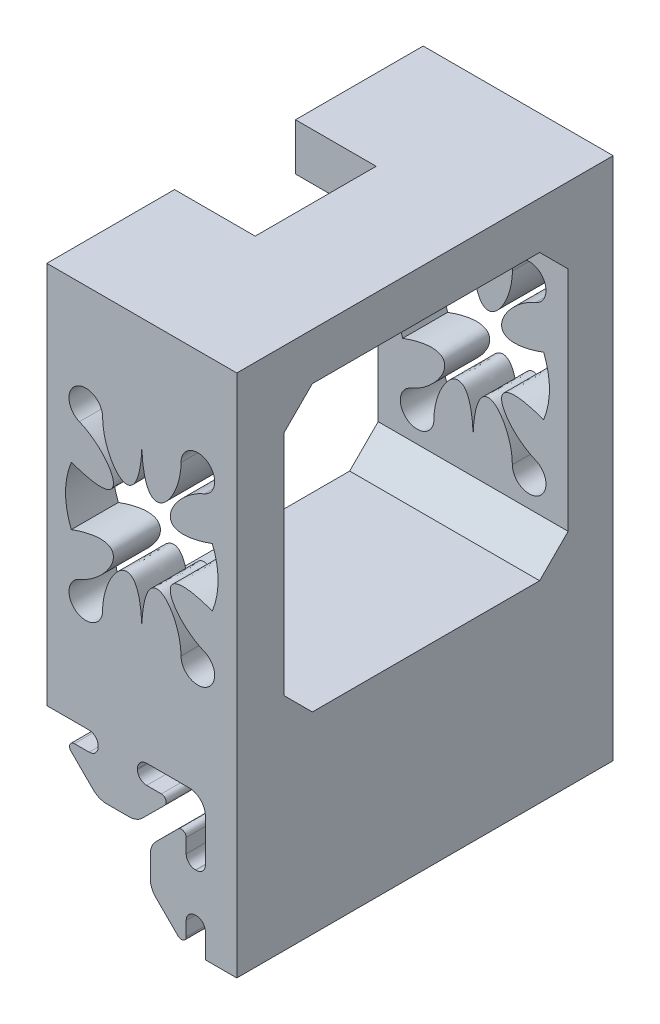
SolidWorks part; units mm, degrees
ref_plane "Front Plane" through (0, 0, 0) normal (0, 0, 1) x (1, 0, 0)
ref_plane "Top Plane" through (0, 0, 0) normal (0, 1, 0) x (1, 0, 0)
ref_plane "Right Plane" through (0, 0, 0) normal (1, 0, 0) x (0, 0, -1)
sketch "Sketch1" plane through (0, 0, 0) normal (0, 0, 1) x (1, 0, 0)
  line L0 (13.02, -7.9417) -> (17.7, -7.9417)
  line L1 (-10.5664, 13.02) -> (-10.5664, 70.02)
  line L2 (-10.5664, 70.02) -> (17.7, 70.02)
  line L3 (17.7, -7.9417) -> (17.7, 70.02)
  line L10 (12.7, -6.3331) -> (12.7, -7.9417) construction
  line L11 (13.02, -5.3171) -> (13.02, -4.2875)
  line L12 (11.651, -2.9185) -> (11.5392, -2.9185)
  line L13 (10.1702, -4.2875) -> (10.1702, -6.4021)
  line L14 (8.9631, -6.9029) -> (5.667, -3.6143)
  line L15 (4.8285, -1.5932) -> (4.8285, 1.5932)
  line L16 (5.667, 3.6143) -> (8.9631, 6.9029)
  line L17 (10.1702, 6.4021) -> (10.1702, 4.2875)
  line L18 (11.5392, 2.9185) -> (11.651, 2.9185)
  line L19 (13.02, 10.5773) -> (13.02, 4.2875)
  line L20 (6.3329, 13.02) -> (10.5626, 13.0198)
  line L22 (6.3329, 13.02) -> (4.2875, 13.02)
  line L23 (2.9185, 11.651) -> (2.9185, 11.5392)
  line L24 (4.2875, 10.1702) -> (6.4768, 10.1702)
  line L25 (6.981, 8.9509) -> (3.6723, 5.6497)
  line L26 (1.6558, 4.8158) -> (-1.6558, 4.8158)
  line L27 (-3.6723, 5.6497) -> (-6.981, 8.9509)
  line L28 (-6.4768, 10.1702) -> (-4.2875, 10.1702)
  line L29 (-2.9185, 11.5392) -> (-2.9185, 11.651)
  line L30 (-4.2875, 13.02) -> (-5.3171, 13.02)
  line L31 (-5.3171, 13.02) -> (-10.5664, 13.02)
  line L32 (13.02, -5.3171) -> (13.02, -7.9417)
  line L33 (13.02, -6.3331) -> (13.02, -7.9417) construction
  line L34 (13.02, 4.2875) -> (13.02, 5.3171) construction
  line L37 (5.3171, 13.02) -> (4.2875, 13.02) construction
  line L38 (-6.3331, 13.02) -> (-9.5504, 13.02) construction
  line L96 (12.7, -5.3171) -> (12.7, -4.2875) construction
  line L97 (11.651, -3.2385) -> (11.5392, -3.2385) construction
  line L98 (10.4902, -4.2875) -> (10.4902, -6.4021) construction
  line L99 (8.7371, -7.1294) -> (5.441, -3.8408) construction
  line L100 (4.5085, -1.5932) -> (4.5085, 1.5932) construction
  line L101 (5.441, 3.8408) -> (8.7371, 7.1294) construction
  line L102 (10.4902, 6.4021) -> (10.4902, 4.2875) construction
  line L103 (11.5392, 3.2385) -> (11.651, 3.2385) construction
  line L104 (12.7, 4.2875) -> (12.7, 5.3171) construction
  line L105 (12.7, 6.3331) -> (12.7, 9.5504) construction
  line L106 (9.5504, 12.7) -> (6.3331, 12.7) construction
  line L107 (5.3171, 12.7) -> (4.2875, 12.7) construction
  line L108 (3.2385, 11.651) -> (3.2385, 11.5392) construction
  line L109 (4.2875, 10.4902) -> (6.4768, 10.4902) construction
  line L110 (7.207, 8.7244) -> (3.8983, 5.4232) construction
  line L111 (1.6558, 4.4958) -> (-1.6558, 4.4958) construction
  line L112 (-3.8983, 5.4232) -> (-7.207, 8.7244) construction
  line L113 (-6.4768, 10.4902) -> (-4.2875, 10.4902) construction
  line L114 (-3.2385, 11.5392) -> (-3.2385, 11.651) construction
  line L115 (-4.2875, 12.7) -> (-5.3171, 12.7) construction
  line L116 (-6.3331, 12.7) -> (-9.5504, 12.7) construction
  arc A0 (13.02, -4.2875) -> (11.651, -2.9185) centre (11.651, -4.2875) ccw
  arc A1 (11.5392, -2.9185) -> (10.1702, -4.2875) centre (11.5392, -4.2875) ccw
  arc A2 (8.9631, -6.9029) -> (10.1702, -6.4021) centre (9.4628, -6.4021) ccw
  arc A3 (4.8285, -1.5932) -> (5.667, -3.6143) centre (7.6835, -1.5932) ccw
  arc A4 (5.667, 3.6143) -> (4.8285, 1.5932) centre (7.6835, 1.5932) ccw
  arc A5 (10.1702, 6.4021) -> (8.9631, 6.9029) centre (9.4628, 6.4021) ccw
  arc A6 (10.1702, 4.2875) -> (11.5392, 2.9185) centre (11.5392, 4.2875) ccw
  arc A7 (11.651, 2.9185) -> (13.02, 4.2875) centre (11.651, 4.2875) ccw
  arc A8 (4.2875, 13.02) -> (2.9185, 11.651) centre (4.2875, 11.651) ccw
  arc A9 (2.9185, 11.5392) -> (4.2875, 10.1702) centre (4.2875, 11.5392) ccw
  arc A10 (6.981, 8.9509) -> (6.4768, 10.1702) centre (6.4768, 9.4563) ccw
  arc A11 (1.6558, 4.8158) -> (3.6723, 5.6497) centre (1.6558, 7.6708) ccw
  arc A12 (-3.6723, 5.6497) -> (-1.6558, 4.8158) centre (-1.6558, 7.6708) ccw
  arc A13 (-6.4768, 10.1702) -> (-6.981, 8.9509) centre (-6.4768, 9.4563) ccw
  arc A14 (-4.2875, 10.1702) -> (-2.9185, 11.5392) centre (-4.2875, 11.5392) ccw
  arc A15 (-2.9185, 11.651) -> (-4.2875, 13.02) centre (-4.2875, 11.651) ccw
  arc A16 (13.02, 10.5773) -> (10.5626, 13.0198) centre (10.5918, 10.5918) ccw
  arc A17 (13.0198, 10.5625) -> (10.5626, 13.0198) centre (10.5918, 10.5918) ccw construction
  arc A114 (12.7, -5.3171) -> (12.7, -6.3331) centre (12.7, -5.8251) ccw construction
  arc A115 (12.7, -4.2875) -> (11.651, -3.2385) centre (11.651, -4.2875) ccw construction
  arc A116 (11.5392, -3.2385) -> (10.4902, -4.2875) centre (11.5392, -4.2875) ccw construction
  arc A117 (8.7371, -7.1294) -> (10.4902, -6.4021) centre (9.4628, -6.4021) ccw construction
  arc A118 (4.5085, -1.5932) -> (5.441, -3.8408) centre (7.6835, -1.5932) ccw construction
  arc A119 (5.441, 3.8408) -> (4.5085, 1.5932) centre (7.6835, 1.5932) ccw construction
  arc A120 (10.4902, 6.4021) -> (8.7371, 7.1294) centre (9.4628, 6.4021) ccw construction
  arc A121 (10.4902, 4.2875) -> (11.5392, 3.2385) centre (11.5392, 4.2875) ccw construction
  arc A122 (11.651, 3.2385) -> (12.7, 4.2875) centre (11.651, 4.2875) ccw construction
  arc A123 (12.7, 6.3331) -> (12.7, 5.3171) centre (12.7, 5.8251) ccw construction
  arc A124 (12.6998, 10.5664) -> (12.7, 9.5504) centre (12.7, 10.0584) ccw construction
  arc A125 (12.6998, 10.5664) -> (10.5664, 12.6998) centre (10.5918, 10.5918) ccw construction
  arc A126 (9.5504, 12.7) -> (10.5664, 12.6998) centre (10.0584, 12.7) ccw construction
  arc A127 (5.3171, 12.7) -> (6.3331, 12.7) centre (5.8251, 12.7) ccw construction
  arc A128 (4.2875, 12.7) -> (3.2385, 11.651) centre (4.2875, 11.651) ccw construction
  arc A129 (3.2385, 11.5392) -> (4.2875, 10.4902) centre (4.2875, 11.5392) ccw construction
  arc A130 (7.207, 8.7244) -> (6.4768, 10.4902) centre (6.4768, 9.4563) ccw construction
  arc A131 (1.6558, 4.4958) -> (3.8983, 5.4232) centre (1.6558, 7.6708) ccw construction
  arc A132 (-3.8983, 5.4232) -> (-1.6558, 4.4958) centre (-1.6558, 7.6708) ccw construction
  arc A133 (-6.4768, 10.4902) -> (-7.207, 8.7244) centre (-6.4768, 9.4563) ccw construction
  arc A134 (-4.2875, 10.4902) -> (-3.2385, 11.5392) centre (-4.2875, 11.5392) ccw construction
  arc A135 (-3.2385, 11.651) -> (-4.2875, 12.7) centre (-4.2875, 11.651) ccw construction
  arc A136 (-6.3331, 12.7) -> (-5.3171, 12.7) centre (-5.8251, 12.7) ccw construction
  arc A137 (-10.5664, 12.6998) -> (-9.5504, 12.7) centre (-10.0584, 12.7) ccw construction
  dimension "D1" = 57
  dimension "D6" = 5
  dimension "D8" = 0.32
  dimension "D7" = 6.2898
  dimension "D9" = 4.2297
extrude "Boss-Extrude1" add sketch "Sketch1" along normal blind 56 contours L3 L2 L1 L31 L30 A15 L29 A14 L28 A13 L27 A12 L26 A11 L25 A10 L24 A9 L23 A8 L22 L20 A16 L19 A7 L18 A6 L17 A5 L16 A4 L15 A3 L14 A2 L13 A1 L12 A0 L11 L32 L0
sketch "Sketch14" plane through (17.7, 0, 0) normal (1, 0, 0) x (0, 0, -1)
  line L0 (-44.7574, 20.72) -> (-10.9426, 20.72)
  line L1 (-6.7, 24.9626) -> (-6.7, 58.7774)
  line L2 (-10.9426, 63.02) -> (-44.7574, 63.02)
  line L3 (-49, 58.7774) -> (-49, 24.9626)
  line L4 (-56, -7.9417) -> (-56, 70.02) construction
  line L6 (-56, 70.02) -> (0, 70.02) construction
  line L7 (-44.7574, 20.72) -> (-49, 24.9626)
  line L8 (-49, 58.7774) -> (-44.7574, 63.02)
  line L9 (-10.9426, 63.02) -> (-6.7, 58.7774)
  line L10 (-10.9426, 20.72) -> (-6.7, 24.9626)
  point P0 (-121.6189, 51.261)
  dimension "D2" = 42.3
  dimension "D3" = 7
  dimension "D4" = 7
  dimension "D5" = 6
  dimension "D6" = 6
  dimension "D7" = 45
  dimension "D8" = 6
  dimension "D9" = 45
  dimension "D10" = 45
  dimension "D11" = 42.3
  dimension "D12" = 6
  dimension "D13" = 45
extrude "Cut-Extrude1" cut sketch "Sketch14" against normal blind 56
sketch "Sketch15" plane through (0, 70.02, 0) normal (0, 1, 0) x (1, 0, 0)
  line L1 (-10.5664, -56) -> (-10.5664, 0) construction
  line L2 (-10.5664, -19) -> (1.4336, -19)
  line L3 (1.4336, -19) -> (1.4336, -37)
  line L4 (1.4336, -37) -> (-10.5664, -37)
  line L6 (-10.5664, -19) -> (-15.1003, -19)
  line L7 (-15.1003, -19) -> (-15.1003, -37)
  line L8 (-15.1003, -37) -> (-10.5664, -37)
  dimension "D3" = 12
extrude "Cut-Extrude2" cut sketch "Sketch15" against normal blind 10
sketch "Sketch17" plane through (0, 0, 0) normal (0, 0, -1) x (-1, 0, 0)
  line L1 (-17.7, 63.02) -> (10.5664, 63.02) construction
  line L2 (-17.7, 63.02) -> (-17.7, 20.72) construction
  line L3 (-17.7, 20.72) -> (10.5664, 20.72) construction
  line L4 (10.5664, 63.02) -> (10.5664, 20.72) construction
  line L5 (10.5664, 13.02) -> (10.5664, 70.02) construction
  line L6 (10.5664, 70.02) -> (-17.7, 70.02) construction
  line L7 (-17.7, 63.02) -> (10.5664, 20.72) construction
  line L8 (10.5664, 63.02) -> (-17.7, 20.72) construction
  line L9 (-17.7, -7.9417) -> (-17.7, 70.02) construction
  line L10 (-3.5668, 63.02) -> (-3.5668, 20.72) construction
  line L11 (-3.5668, 41.87) -> (-11.5383, 41.87) construction
  line L12 (-13.02, -7.9417) -> (-17.7, -7.9417) construction
  arc A0 (-9.4008, 54.3417) -> (-12.8574, 52.0319) centre (-11.9008, 54.3417) ccw
  arc A1 (-14.0534, 46.2127) -> (-14.0534, 37.5273) centre (-3.5668, 41.87) ccw
  arc A2 (2.2673, 29.3983) -> (5.7238, 31.7081) centre (4.7673, 29.3983) ccw
  arc A3 (-12.8574, 31.7081) -> (-9.4008, 29.3983) centre (-11.9008, 29.3983) ccw
  arc A4 (5.7238, 52.0319) -> (2.2673, 54.3417) centre (4.7673, 54.3417) ccw
  arc A5 (6.9199, 37.5273) -> (6.9199, 46.2127) centre (-3.5668, 41.87) ccw
  spline S0 degree 3 poles (-9.4008, 54.3417) (-9.4008, 48.8351) (-4.0396, 42.6941) (-3.5668, 53.2203) knots 0 0 0 0 1 1 1 1
  spline S1 degree 3 poles (-12.8574, 52.0319) (-7.7697, 49.925) (-4.1473, 42.6222) (-14.0534, 46.2127) knots 0 0 0 0 1 1 1 1
  spline S2 degree 3 poles (5.7238, 52.0319) (0.6362, 49.925) (-2.9863, 42.6222) (6.9199, 46.2127) knots 0 0 0 0 1 1 1 1
  spline S3 degree 3 poles (2.2673, 54.3417) (2.2673, 48.8351) (-3.0939, 42.6941) (-3.5668, 53.2203) knots 0 0 0 0 1 1 1 1
  spline S4 degree 3 poles (5.7238, 31.7081) (0.6362, 33.815) (-2.9863, 41.1178) (6.9199, 37.5273) knots 0 0 0 0 1 1 1 1
  spline S5 degree 3 poles (2.2673, 29.3983) (2.2673, 34.9049) (-3.0939, 41.0459) (-3.5668, 30.5197) knots 0 0 0 0 1 1 1 1
  spline S6 degree 3 poles (-9.4008, 29.3983) (-9.4008, 34.9049) (-4.0396, 41.0459) (-3.5668, 30.5197) knots 0 0 0 0 1 1 1 1
  spline S7 degree 3 poles (-12.8574, 31.7081) (-7.7697, 33.815) (-4.1473, 41.1178) (-14.0534, 37.5273) knots 0 0 0 0 1 1 1 1
  point P6 (-3.5668, 53.2203)
  point P11 (-89.3215, 49.3113)
  point P19 (-3.5668, 41.87)
other "AlignGroup1" parameters "D4"=3.1557, "D6"=11.3503, "D1"=32.1288, "D2"=28.2664, "D3"=28.2664, "D5"=50.8752, "D7"=6.7478, "D8"=42.3, "D9"=3.1506, "D10"=1.0803, "D11"=0.3414, "D12"=3.1506, "D13"=1.0803, "D14"=0.1626
extrude "Cut-Extrude3" cut sketch "Sketch17" against normal through all both and the other way through all
